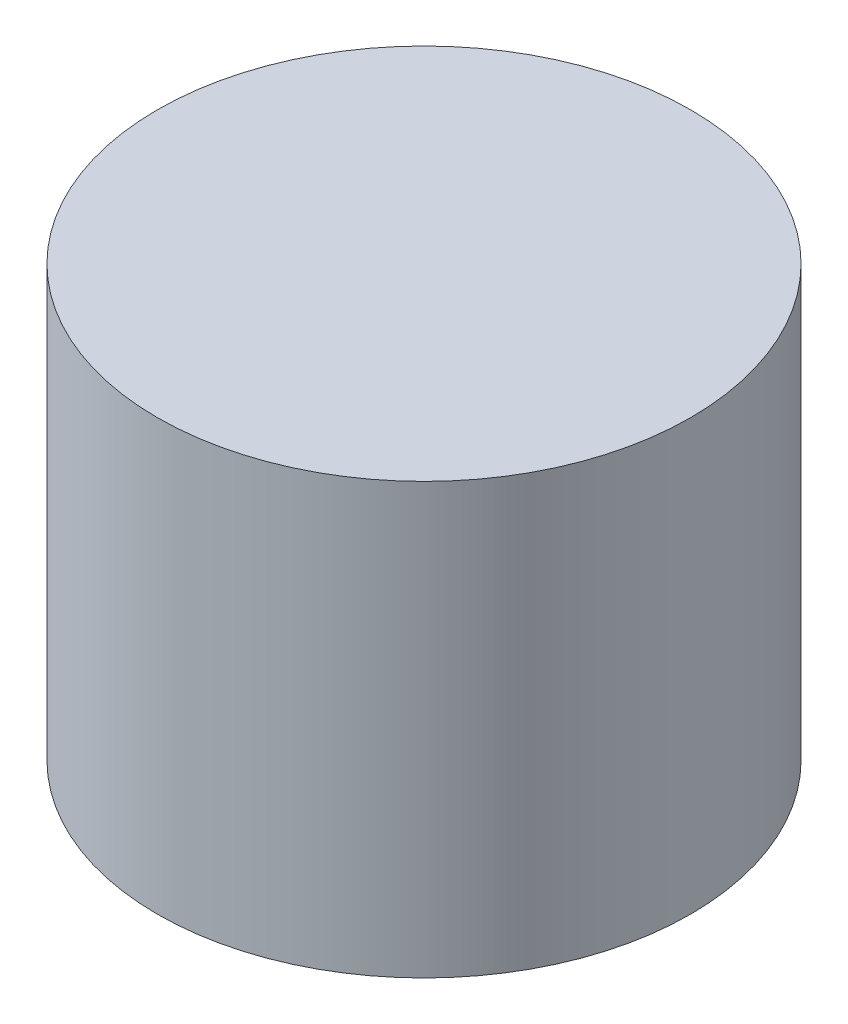
SolidWorks part; units mm, degrees
other "标注1"
sketch "草图2" plane through (46.5, 75, 46.5) normal (0.8745, 0.2803, 0.3958) x (0.4218, -0.0367, -0.906)
ref_plane "前视基准面" through (0, 0, 0) normal (0, 0, 1) x (1, 0, 0)
ref_plane "上视基准面" through (0, 0, 0) normal (0, 1, 0) x (1, 0, 0)
ref_plane "右视基准面" through (0, 0, 0) normal (1, 0, 0) x (0, 0, -1)
other "Configuration Table"
sketch "草图1" plane through (0, 0, 0) normal (0, 1, 0) x (1, 0, 0)
  circle A0 centre (0, 0) radius 46.5
  dimension "D1" = 93
extrude "凸台-拉伸1" add sketch "草图1" along normal blind 75
